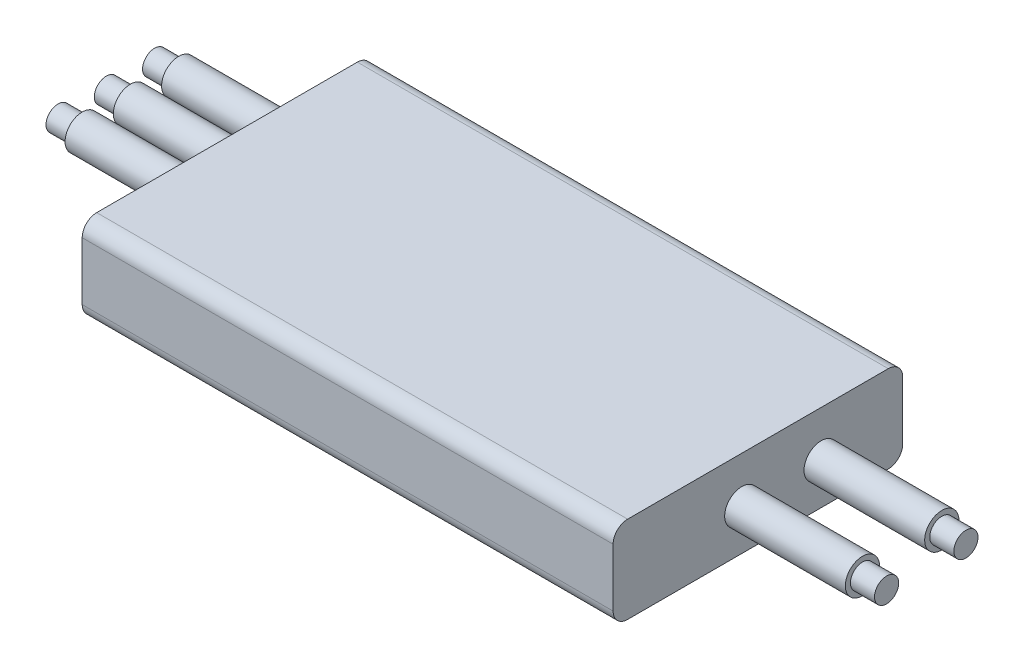
SolidWorks part; units mm, degrees
ref_plane "Front Plane" through (0, 0, 0) normal (0, 0, 1) x (1, 0, 0)
ref_plane "Top Plane" through (0, 0, 0) normal (0, 1, 0) x (1, 0, 0)
ref_plane "Right Plane" through (0, 0, 0) normal (1, 0, 0) x (0, 0, -1)
sketch "Sketch1" plane through (0, 0, 0) normal (0, 1, 0) x (1, 0, 0)
  line L1 (-55, -30) -> (55, -30)
  line L2 (-55, -30) -> (-55, 30)
  line L3 (-55, 30) -> (55, 30)
  line L4 (55, -30) -> (55, 30)
  line L5 (-55, -30) -> (55, 30) construction
  line L6 (-55, 30) -> (55, -30) construction
  point P0 (0, 0)
  dimension "D1" = 110
  dimension "D2" = 60
extrude "Boss-Extrude1" add sketch "Sketch1" along normal blind 18
fillet "Fillet1" radius 3 4 edges at (0, 0, -30) (0, 18, -30) (0, 0, 30) (0, 18, 30)
sketch "Sketch2" plane through (55, 0, 0) normal (1, 0, 0) x (0, 0, -1)
  circle A0 centre (13.0907, 8.4673) radius 3.55
  circle A1 centre (-3.3456, 8.4673) radius 3.55
  dimension "D1" = 7.1
extrude "Boss-Extrude2" add sketch "Sketch2" along normal blind 25
sketch "Sketch3" plane through (-55, 0, 0) normal (-1, 0, 0) x (0, 0, 1)
  line L0 (-27, 0) -> (27, 0) construction
  line L1 (-30, 15) -> (-30, 3) construction
  circle A0 centre (-15, 9) radius 3.55
  circle A1 centre (5, 9) radius 3.55
  circle A2 centre (-5, 9) radius 3.55
  dimension "D1" = 7.1
  dimension "D2" = 10
  dimension "D3" = 10
  dimension "D4" = 9
  dimension "D5" = 15
extrude "Boss-Extrude3" add sketch "Sketch3" along normal blind 25
sketch "Sketch4" plane through (-80, 0, 0) normal (-1, 0, 0) x (0, 0, 1)
  circle A0 centre (-15, 9) radius 2.5
  circle A1 centre (-5, 9) radius 2.5
  circle A2 centre (5, 9) radius 2.5
  circle A3 centre (-15, 9) radius 3.55 construction
  circle A4 centre (-5, 9) radius 3.55 construction
  circle A5 centre (5, 9) radius 3.55 construction
  dimension "D1" = 5
extrude "Boss-Extrude4" add sketch "Sketch4" along normal blind 5
sketch "Sketch5" plane through (80, 0, 0) normal (1, 0, 0) x (0, 0, -1)
  circle A0 centre (-3.3456, 8.4673) radius 2.5
  circle A1 centre (13.0907, 8.4673) radius 2.5
  circle A2 centre (-3.3456, 8.4673) radius 3.55 construction
  dimension "D1" = 5
extrude "Boss-Extrude5" add sketch "Sketch5" along normal blind 5
